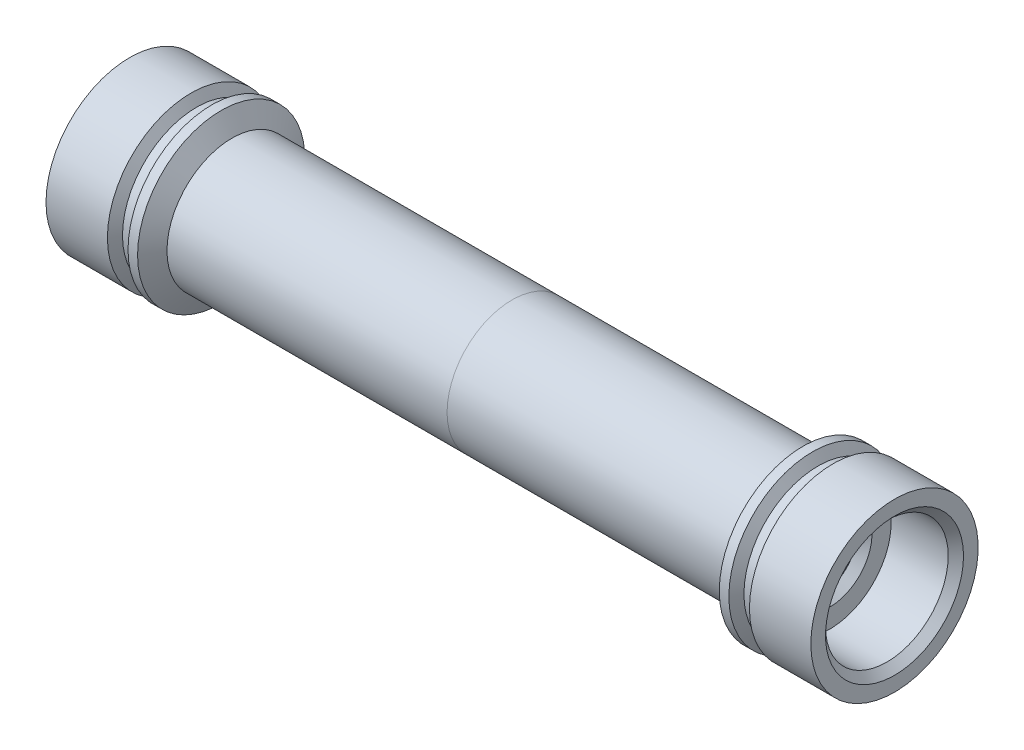
SolidWorks part; units mm, degrees
ref_plane "Front Plane" through (0, 0, 0) normal (0, 0, 1) x (1, 0, 0)
ref_plane "Top Plane" through (0, 0, 0) normal (0, 1, 0) x (1, 0, 0)
ref_plane "Right Plane" through (0, 0, 0) normal (1, 0, 0) x (0, 0, -1)
sketch "Sketch2" plane through (0, 0, 0) normal (0, 0, 1) x (1, 0, 0)
  line L0 (0, 0) -> (0, 28.4375) construction
  line L1 (-25.4, 4.075) -> (-21.1, 4.075) construction
  line L2 (-25.4, 4.075) -> (-25.4, -4.075) construction
  line L3 (-25.4, -4.075) -> (-21.1, -4.075) construction
  line L4 (-21.1, 4.075) -> (-21.1, -4.075) construction
  line L5 (-25.4, 4.075) -> (-21.1, -4.075) construction
  line L6 (-25.4, -4.075) -> (-21.1, 4.075) construction
  line L7 (21.1, 4.5) -> (42.4832, 4.5) construction
  line L8 (21.1, 4.5) -> (21.1, -4.5) construction
  line L9 (21.1, -4.5) -> (42.4832, -4.5) construction
  line L10 (42.4832, 4.5) -> (42.4832, -4.5) construction
  line L11 (21.1, 4.5) -> (42.4832, -4.5) construction
  line L12 (21.1, -4.5) -> (42.4832, 4.5) construction
  line L13 (-25.4, 0) -> (42.4832, 0) construction
  line L14 (-25.4, 5.5562) -> (-21.3216, 5.5562)
  line L21 (-18.6035, 4.318) -> (0, 4.318)
  line L22 (-25.4, 5.5562) -> (-25.4, 4.075)
  line L23 (-25.4, 4.075) -> (-21.1, 4.075)
  line L24 (-21.1, 4.075) -> (-21.1, 0)
  line L25 (-21.1, 0) -> (0, 0)
  line L26 (0, 0) -> (0, 4.318)
  line L27 (-30.6688, -5.5562) -> (-30.6688, 5.5562) construction
  line L28 (-21.3216, 5.5562) -> (-20.955, 4.9212)
  line L29 (-20.955, 4.9212) -> (-20.32, 4.9212)
  line L30 (-25.4, 5.5562) -> (25.4, 5.5562) construction
  line L31 (0, 1.625) -> (-12.5, 1.625)
  line L32 (-12.5, 1.625) -> (-14.125, 0)
  line L33 (-12.5, 1.625) -> (-12.5, -1.625) construction
  line L34 (-12.5, 1.625) -> (12.5, 1.625) construction
  line L35 (-21.1, 1.905) -> (-15.448, 1.905)
  line L36 (-15.448, 1.905) -> (-15.448, 0)
  line L37 (-21.1, 2.805) -> (-20.592, 2.297)
  line L38 (-15.448, 1.905) -> (-28.448, 1.905) construction
  line L39 (-15.448, 1.905) -> (-15.448, -1.905) construction
  line L40 (-15.448, -1.905) -> (-28.448, -1.905) construction
  line L41 (-28.448, 1.905) -> (-28.448, -1.905) construction
  line L42 (-20.592, 2.297) -> (-20.592, 0)
  line L46 (-20.32, 4.9212) -> (-19.9534, 5.5562)
  line L47 (-19.9534, 5.5562) -> (-19.3184, 5.5562)
  line L48 (-19.3184, 5.5562) -> (-18.6035, 4.318)
  line L49 (-20.6375, 4.9212) -> (-20.6375, 8.7882) construction
  line L50 (-20.6375, 8.7882) -> (20.6375, 8.7882) construction
  point P0 (-23.25, 0)
  point P5 (31.7916, 0)
  point P27 (-30.6688, 0)
  point P29 (-12.5, 0)
  point P33 (0, 8.7882)
  point P36 (0, 1.625)
  point P48 (-15.448, 0)
  point P51 (0, 5.5562)
  dimension "D3" = 4.318
  dimension "D4" = 11.1125
  dimension "D5" = 8.15
  dimension "D13" = 45
  dimension "D14" = 25
  dimension "D15" = 3.25
  dimension "D16" = 3.81
  dimension "D17" = 3.048
  dimension "D18" = 1.27
  dimension "D19" = 0.508
  dimension "D20" = 45
  dimension "D21" = 13
  dimension "D11" = 50.8
  dimension "D6" = 60
  dimension "D7" = 0.635
  dimension "D8" = 60
  dimension "D9" = 41.275
  dimension "D10" = 0.635
  dimension "D12" = 0.635
  dimension "D22" = 4.3
revolve "Revolve1" add sketch "Sketch2" angle 360 about L13
chamfer "Chamfer1" distance 0.508 angle 45 1 edges at (-25.4, 0, 4.075)
mirror "Mirror1" about plane through (0, 0, 0) normal (1, 0, 0) of bodies 101
equation "\"D15@Sketch2\"=3mm+.25mm"
equation "\"D22@Sketch2\"=4.3mm"
